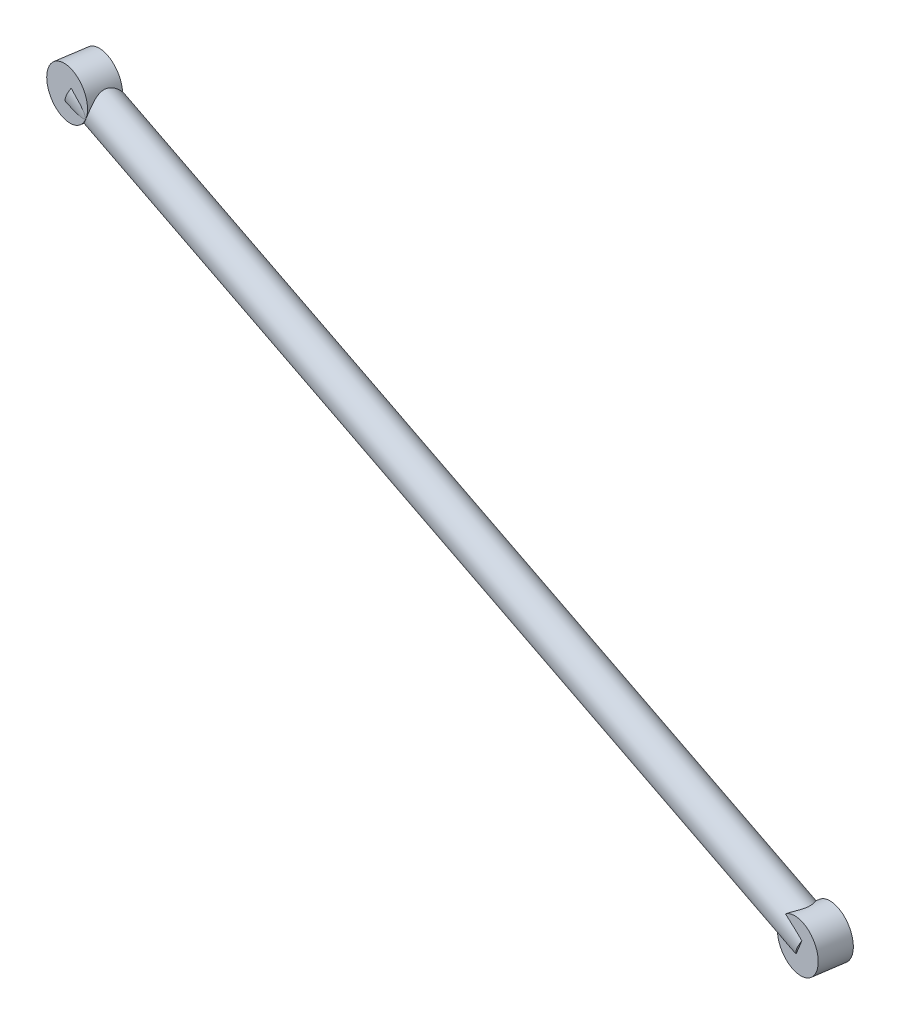
SolidWorks part; units mm, degrees
ref_plane "Plano frontal" through (0, 0, 0) normal (0, 0, 1) x (1, 0, 0)
ref_plane "Plano superior" through (0, 0, 0) normal (0, 1, 0) x (1, 0, 0)
ref_plane "Plano direito" through (0, 0, 0) normal (1, 0, 0) x (0, 0, -1)
sketch3d "SUSP_RL_toe_link_eixo"
  line L0 (-175, 1319.6, -94) -> (-520.81, 1474.2, -108.53)
sweep "SUSP_RL_toe_link" add path "SUSP_RL_toe_link_eixo" circular profile diameter 16 parameters "D3"=16
sketch3d "SUSP_RL_toe_link_rod_end_in_eixo"
  line L0 (-176.0347, 1319.6, -87.0769) -> (-173.9653, 1319.6, -100.9231)
sweep "SUSP_RL_toe_link_rod_end_in" add path "SUSP_RL_toe_link_rod_end_in_eixo" circular profile diameter 22 parameters "D3"=22
sketch3d "SUSP_RL_toe_link_rod_end_out_eixo"
  line L0 (-521.8447, 1474.2, -101.6069) -> (-519.7753, 1474.2, -115.4531)
sweep "SUSP_RL_toe_link_rod_end_out" add path "SUSP_RL_toe_link_rod_end_out_eixo" circular profile diameter 22 parameters "D3"=22
sketch3d "REF_SKETCH"
  line L0 (-179, 1317.2, -95.8) -> (-171, 1322, -92.2)
  line L1 (-172.6, 1316.6, -97.2) -> (-177.4, 1322.6, -90.8)
  line L2 (-524.81, 1471.8, -110.33) -> (-516.81, 1476.6, -106.73)
  line L3 (-518.41, 1471.2, -111.73) -> (-523.21, 1477.2, -105.33)
ref_point "P_IN"
ref_point "P_OUT"
